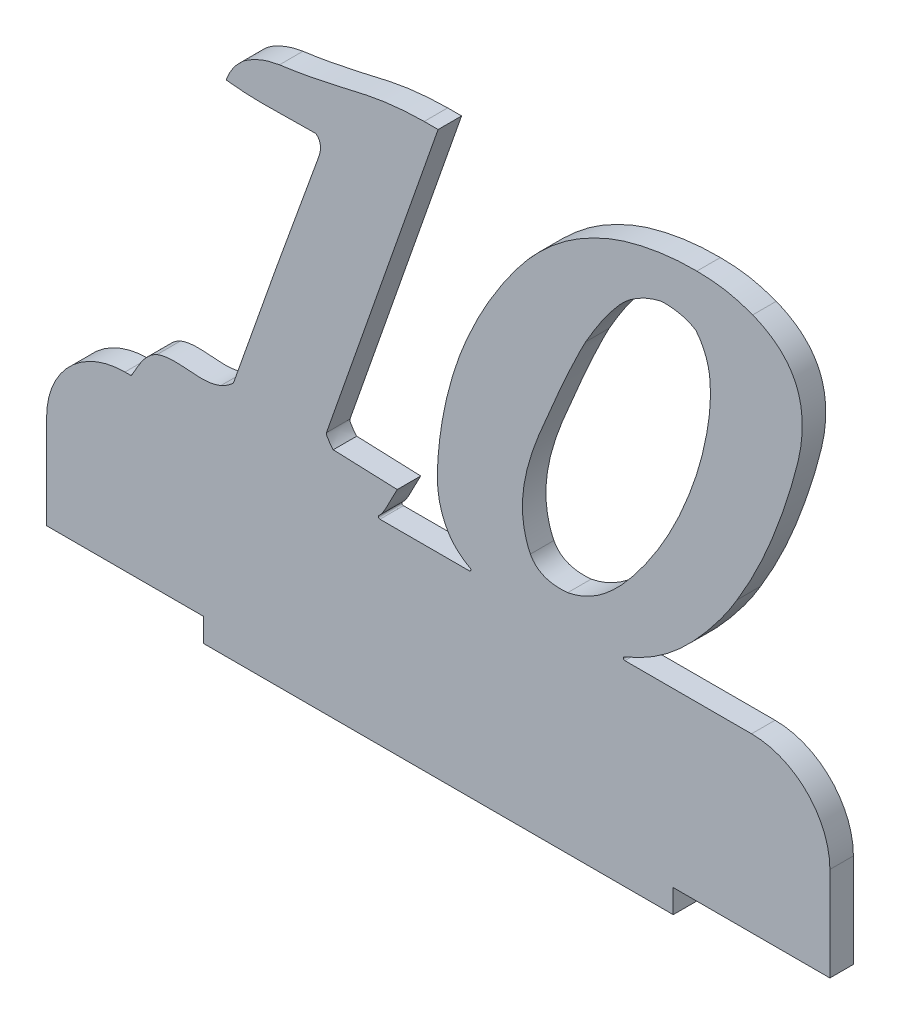
SolidWorks part; units mm, degrees
ref_plane "Front Plane" through (0, 0, 0) normal (0, 0, 1) x (1, 0, 0)
ref_plane "Top Plane" through (0, 0, 0) normal (0, 1, 0) x (1, 0, 0)
ref_plane "Right Plane" through (0, 0, 0) normal (1, 0, 0) x (0, 0, -1)
sketch "Sketch1" plane through (0, 0, 0) normal (0, 0, 1) x (1, 0, 0)
  line L0 (0, 20) -> (100, 20) construction
  line L1 (41.9538, 22) -> (54.8964, 22)
  line L2 (0, 22) -> (0, 0)
  line L3 (0, 0) -> (20, 0)
  line L4 (100, 22) -> (100, 0)
  line L5 (0, 22) -> (10.8106, 22)
  line L6 (72.7527, 22) -> (100, 22)
  line L7 (49.9806, 68.8033) -> (35.7312, 28.1661)
  line L8 (36.5913, 26.7001) -> (44.7617, 26.3873)
  line L11 (80, 0) -> (100, 0)
  line L13 (20, 0) -> (20, -3)
  line L14 (20, -3) -> (80, -3)
  line L15 (80, 0) -> (80, -3)
  spline S0 degree 3 poles (44.7617, 26.3873) (44.1668, 25.3741) (43.6216, 24.0519) (42.7236, 22.5857) (42.2645, 22.2071) (41.9976, 22.0283) (41.9538, 22) knots 0 0 0 0 0.504343 0.619768 0.735364 0.757778 0.757778 0.757778 0.757778
  spline S1 degree 3 poles (10.8106, 22) (10.9376, 22.2095) (11.3085, 22.8541) (12.1578, 24.3778) (13.1525, 25.5474) (14.0932, 25.9768) knots 0.126257 0.126257 0.126257 0.126257 0.248912 0.498933 1 1 1 1
  spline S2 degree 3 poles (14.0932, 25.9768) (15.4346, 26.4961) (18.1853, 26.2213) (20.9547, 26.0657) (22.2637, 26.6414) knots 0 0 0 0 0.501452 1 1 1 1
  spline S3 degree 2 poles (22.2637, 26.6414) (23.1452, 27.0319) (23.8469, 27.6969) knots 0 0 0 1 1 1
  spline S4 degree 3 poles (23.8469, 27.6969) (25.6292, 32.7321) (29.1542, 42.8549) (32.8433, 52.9191) (34.6757, 57.9745) knots 0 0 0 0 0.498323 1 1 1 1
  spline S5 degree 3 poles (34.6757, 57.9745) (34.8589, 58.472) (35.1541, 59.4386) (34.7015, 60.35) (34.3434, 60.5546) knots 0 0 0 0 0.581397 1 1 1 1
  spline S6 degree 3 poles (34.3434, 60.5546) (32.4267, 60.5884) (28.6217, 60.4045) (24.8087, 60.5093) (22.9283, 60.7501) knots 0 0 0 0 0.503015 1 1 1 1
  spline S7 degree 3 poles (22.9283, 60.7501) (23.1602, 61.4173) (23.6445, 62.3662) (24.5625, 63.427) (25.3357, 64.1495) (26.2837, 64.7032) (27.7107, 65.3859) (28.9028, 65.7007) (29.7304, 65.8322) knots 0 0 0 0 0.237267 0.352024 0.469659 0.590381 0.718477 1 1 1 1
  spline S8 degree 3 poles (29.7304, 65.8322) (32.8427, 66.2306) (36.7045, 67.0826) (41.3263, 68.1625) (44.4062, 68.6449) (46.6993, 68.7925) (48.2019, 68.8033) knots 0 0 0 0 0.501478 0.63281 0.759518 1 1 1 1
  spline S9 degree 3 poles (48.2019, 68.8033) (48.4104, 68.8033) (49.0033, 68.8033) (49.5962, 68.8033) (49.9806, 68.8033) knots 0 0 0 0 0.351648 1 1 1 1
  spline S10 degree 3 poles (35.7312, 28.1661) (35.678, 27.9663) (36.0097, 27.4566) (36.2874, 26.9738) (36.5913, 26.7001) knots 0 0 0 0 0.324502 1 1 1 1
  spline S11 degree 3 poles (82.8774, 63.0566) (82.2762, 63.4661) (80.8109, 63.9723) (79.2731, 64.0996) (78.4599, 64.0535) knots 0 0 0 0 0.469699 1 1 1 1
  spline S12 degree 3 poles (78.4599, 64.0535) (77.3152, 63.8128) (75.6972, 63.1353) (73.8088, 61.7577) (71.5009, 59.1796) (69.9672, 56.728) (68.8235, 54.7493) knots 0 0 0 0 0.25259 0.375811 0.50377 1 1 1 1
  spline S13 degree 3 poles (68.8235, 54.7493) (68.3672, 53.9513) (67.769, 52.6347) (66.8775, 50.8156) (66.164, 49.2341) (65.3996, 47.5149) (64.5991, 45.6481) (63.7425, 43.6519) (62.8705, 41.5636) (62.0775, 39.4654) (61.4458, 37.4381) (61.005, 35.531) (60.7621, 33.7379) (60.7148, 32.0587) (60.9165, 30.033) (61.336, 28.6093) (61.7672, 27.7556) knots 0 0 0 0 0.095871 0.150957 0.21155 0.277044 0.347448 0.42366 0.503899 0.583776 0.657815 0.725493 0.787949 0.846481 0.90051 1 1 1 1
  spline S14 degree 3 poles (61.7672, 27.7556) (62.1256, 27.0126) (63.6251, 25.8053) (65.538, 25.7887) (66.517, 25.8596) knots 0 0 0 0 0.446154 1 1 1 1
  spline S15 degree 3 poles (66.517, 25.8596) (67.9745, 26.1339) (70.1311, 27.1523) (72.6634, 29.3201) (74.6139, 31.4773) (76.4807, 33.9628) (78.2422, 36.6368) (79.8326, 39.4633) (81.2272, 42.4196) (82.4253, 45.4365) (83.4169, 48.4486) (84.1355, 51.4371) (84.6401, 54.3277) (84.8097, 57.0295) (84.6078, 60.06) (83.733, 62.0486) (82.8774, 63.0566) knots 0 0 0 0 0.099523 0.157976 0.224341 0.295662 0.367825 0.440561 0.514606 0.588508 0.65979 0.72866 0.796042 0.857776 0.911265 1 1 1 1
  spline S16 degree 3 poles (54.8964, 22) (54.6605, 22.0904) (53.9598, 22.3904) (52.9001, 23.0798) (51.7901, 24.0989) (50.9602, 25.3761) (50.3547, 26.8477) (49.8011, 29.2125) (49.8707, 31.1322) (49.9611, 32.4467) knots 0.534066 0.534066 0.534066 0.534066 0.5623 0.61932 0.674488 0.729675 0.788153 0.851799 1 1 1 1
  spline S17 degree 3 poles (49.9611, 32.4467) (50.128, 34.6748) (50.6172, 38.0004) (51.7466, 42.3372) (52.8094, 45.5466) (54.164, 48.6799) (55.702, 51.7858) (57.5098, 54.8289) (59.5169, 57.796) (61.7144, 60.5854) (64.1887, 63.0042) (66.8309, 65.0918) (69.7111, 66.7392) (72.7466, 68.0871) (77.1691, 69.3094) (80.6478, 69.6941) (83.0143, 69.6633) knots 0 0 0 0 0.122246 0.183381 0.245051 0.307032 0.370011 0.434579 0.500535 0.565958 0.62848 0.689454 0.749684 0.809559 0.870725 1 1 1 1
  spline S18 degree 3 poles (83.0143, 69.6633) (84.2745, 69.6529) (86.7173, 69.5094) (89.0575, 68.7995) (90.1487, 68.3928) knots 0 0 0 0 0.519885 1 1 1 1
  spline S19 degree 3 poles (90.1487, 68.3928) (91.4163, 67.8775) (93.2113, 66.8842) (94.9507, 64.9012) (95.8602, 63.2278) (96.3755, 61.3228) (96.5408, 59.2058) (96.3477, 56.875) (95.5983, 53.5356) (94.3197, 49.3692) (92.0186, 43.0656) (89.8216, 38.6393) (88.155, 35.8869) knots 0 0 0 0 0.111906 0.162582 0.212593 0.265416 0.321766 0.384451 0.454781 0.599581 0.738515 1 1 1 1
  spline S20 degree 3 poles (88.155, 35.8869) (87.0635, 34.0297) (85.1932, 31.4592) (82.4439, 28.3363) (80.2752, 26.267) (77.8927, 24.4593) (75.3584, 23.0447) (73.5964, 22.3081) (72.7527, 22) knots 0 0 0 0 0.25786 0.380114 0.498337 0.616577 0.737567 0.845153 0.845153 0.845153 0.845153
  dimension "D1" = 100
  dimension "D2" = 3
  dimension "D3" = 20
  dimension "D4" = 20
  dimension "D5" = 20
extrude "Boss-Extrude1" add sketch "Sketch1" along normal blind 3
fillet "Fillet1" radius 10 2 edges at (0, 22, 1.5) (100, 22, 1.5)
fillet "Fillet2" radius 0.2 4 edges at (72.7527, 22, 1.5) (54.8964, 22, 1.5) (41.9538, 22, 1.5) (10.8106, 22, 1.5)
